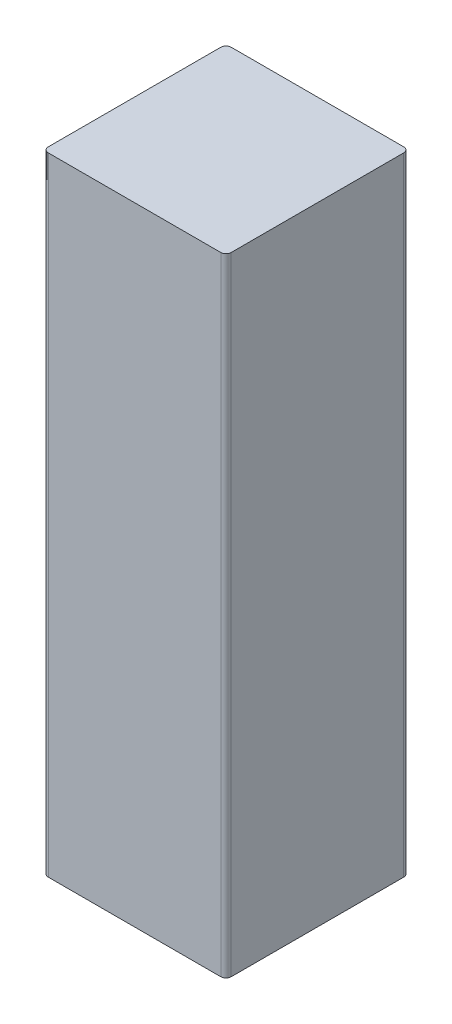
SolidWorks part; units mm, degrees
ref_plane "Front" through (0, 0, 0) normal (0, 0, 1) x (1, 0, 0)
ref_plane "Top" through (0, 0, 0) normal (0, 1, 0) x (1, 0, 0)
ref_plane "Right" through (0, 0, 0) normal (1, 0, 0) x (0, 0, -1)
sketch "Sketch1" plane through (0, 0, 0) normal (0, 1, 0) x (1, 0, 0)
  line L1 (-44.45, 44.45) -> (44.45, 44.45)
  line L2 (-44.45, 44.45) -> (-44.45, -44.45)
  line L3 (-44.45, -44.45) -> (44.45, -44.45)
  line L4 (44.45, 44.45) -> (44.45, -44.45)
  line L5 (-44.45, 44.45) -> (44.45, -44.45) construction
  line L6 (-44.45, -44.45) -> (44.45, 44.45) construction
  point P0 (0, 0)
  dimension "D1" = 88.9
  dimension "D2" = 88.9
extrude "Boss-Extrude1" add sketch "Sketch1" along normal blind 304.8
fillet "Fillet1" radius 2.54 4 edges at (-44.45, 152.4, -44.45) (-44.45, 152.4, 44.45) (44.45, 152.4, -44.45) (44.45, 152.4, 44.45)
equation "\"L\" = 12"
equation "\"D1@Boss-Extrude1\"=\"L\""
